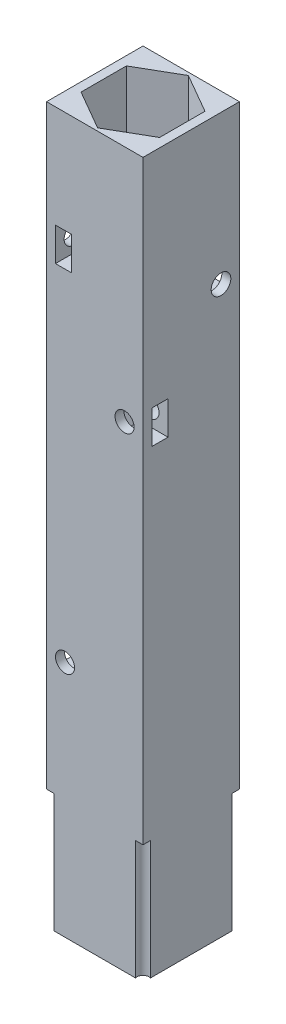
SolidWorks part; units mm, degrees
ref_plane "Спереди" through (0, 0, 0) normal (0, 0, 1) x (1, 0, 0)
ref_plane "Сверху" through (0, 0, 0) normal (0, 1, 0) x (1, 0, 0)
ref_plane "Справа" through (0, 0, 0) normal (1, 0, 0) x (0, 0, -1)
sketch "Эскиз1" plane through (0, 0, 0) normal (0, 1, 0) x (1, 0, 0)
  line L1 (-8.1, -8.1) -> (8.1, -8.1)
  line L2 (-8.1, -8.1) -> (-8.1, 8.1)
  line L3 (-8.1, 8.1) -> (8.1, 8.1)
  line L4 (8.1, -8.1) -> (8.1, 8.1)
  line L5 (-8.1, -8.1) -> (8.1, 8.1) construction
  line L6 (-8.1, 8.1) -> (8.1, -8.1) construction
  circle A0 centre (0, 0) radius 4
  point P0 (0, 0)
  dimension "D3" = 8
  dimension "D1" = 16.2
  dimension "D2" = 16.2
extrude "Бобышка-Вытянуть1" add sketch "Эскиз1" along normal blind 120
sketch "Эскиз2" plane through (0, 0, 0) normal (0, -1, 0) x (1, 0, 0)
  circle A0 centre (-7.8, -7.8) radius 1
  circle A1 centre (-7.8, 7.8) radius 1
  circle A2 centre (7.8, 7.8) radius 1
  circle A3 centre (7.8, -7.8) radius 1
  point P12 (0, 0)
  dimension "D1" = 2
  dimension "D2" = 7.8
  dimension "D3" = 7.8
  dimension "D4" = 4
extrude "Вырез-Вытянуть1" cut sketch "Эскиз2" against normal blind 20
sketch "Эскиз3" plane through (0, 120, 0) normal (0, 1, 0) x (1, 0, 0)
  line L1 (0, 7.621) -> (-6.6, 3.8105)
  line L2 (-6.6, 3.8105) -> (-6.6, -3.8105)
  line L3 (-6.6, -3.8105) -> (0, -7.621)
  line L4 (0, -7.621) -> (6.6, -3.8105)
  line L5 (6.6, -3.8105) -> (6.6, 3.8105)
  line L6 (6.6, 3.8105) -> (0, 7.621)
  circle A0 centre (0, 0) radius 6.6 construction
  dimension "D1" = 13.2
extrude "Вырез-Вытянуть2" cut sketch "Эскиз3" against normal blind 10
sketch "Эскиз4" plane through (0, 0, 8.1) normal (0, 0, 1) x (1, 0, 0)
  circle A0 centre (-5, 40) radius 1.6
  circle A1 centre (5, 80) radius 1.6
  dimension "D1" = 3.2
  dimension "D2" = 3.2
  dimension "D3" = 40
  dimension "D4" = 40
  dimension "D5" = 5
  dimension "D6" = 5
extrude "Вырез-Вытянуть3" cut sketch "Эскиз4" against normal blind 10
ref_plane "Плоскость1" through (0, 0, 6.6) normal (0, 0, 1) x (1, 0, 0)
sketch "Эскиз5" plane through (0, 0, 6.6) normal (0, 0, 1) x (1, 0, 0)
  line L0 (-6.6166, 42.8) -> (-8.1, 42.8)
  line L1 (-1.7668, 40) -> (-3.3834, 42.8)
  line L2 (-3.3834, 42.8) -> (-6.6166, 42.8)
  line L3 (8.1, 120) -> (8.1, 20) construction
  line L4 (-8.1, 120) -> (-8.1, 20) construction
  line L6 (-8.1, 42.8) -> (-8.1, 37.2)
  line L7 (6.6166, 82.8) -> (8.1, 82.8)
  line L8 (1.7668, 80) -> (3.3834, 77.2)
  line L9 (3.3834, 77.2) -> (6.6166, 77.2)
  line L10 (8.1, 82.8) -> (8.1, 77.2)
  line L11 (8.1, 77.2) -> (6.6166, 77.2)
  line L12 (6.6166, 82.8) -> (3.3834, 82.8)
  line L13 (-6.6166, 37.2) -> (-3.3834, 37.2)
  line L14 (-3.3834, 37.2) -> (-1.7668, 40)
  line L15 (-8.1, 37.2) -> (-6.6166, 37.2)
  line L16 (3.3834, 82.8) -> (1.7668, 80)
  line L17 (8.2332, 80) -> (6.6166, 82.8) [skipped]
  line L18 (6.6166, 77.2) -> (8.2332, 80) [skipped]
  line L24 (-6.6166, 42.8) -> (-8.2332, 40) [skipped]
  line L25 (-8.2332, 40) -> (-6.6166, 37.2) [skipped]
  circle A0 centre (-5, 40) radius 2.8 construction
  circle A1 centre (5, 80) radius 2.8 construction
extrude "Вырез-Вытянуть4" cut sketch "Эскиз5" against normal blind 2.7
sketch "Эскиз6" plane through (0, 0, -8.1) normal (0, 0, -1) x (-1, 0, 0)
  circle A0 centre (5, 105) radius 1.65
  dimension "D1" = 3.3
  dimension "D2" = 105
extrude "Вырез-Вытянуть5" cut sketch "Эскиз6" against normal blind 10
ref_plane "Плоскость2" through (0, 0, -6.6) normal (0, 0, -1) x (-1, 0, 0)
sketch "Эскиз7" plane through (0, 0, -6.6) normal (0, 0, -1) x (-1, 0, 0)
  line L0 (6.6166, 107.8) -> (8.1, 107.8)
  line L1 (1.7668, 105) -> (3.3834, 102.2)
  line L2 (3.3834, 102.2) -> (6.6166, 102.2)
  line L4 (8.1, 120) -> (8.1, 20) construction
  line L5 (8.1, 107.8) -> (8.1, 102.2)
  line L6 (6.6166, 107.8) -> (3.3834, 107.8)
  line L7 (3.3834, 107.8) -> (1.7668, 105)
  line L8 (8.1, 102.2) -> (6.6166, 102.2)
  line L12 (8.2332, 105) -> (6.6166, 107.8) [skipped]
  line L13 (6.6166, 102.2) -> (8.2332, 105) [skipped]
  circle A0 centre (5, 105) radius 2.8 construction
extrude "Вырез-Вытянуть6" cut sketch "Эскиз7" against normal blind 2.7
ref_plane "Плоскость3" through (-6.6, 0, 0) normal (-1, 0, 0) x (0, 0, 1)
ref_plane "Плоскость4" through (6.6, 0, 0) normal (1, 0, 0) x (0, 0, -1)
sketch "Эскиз9" plane through (-8.1, 0, 0) normal (-1, 0, 0) x (0, 0, 1)
  circle A0 centre (5, 100) radius 1.65
  dimension "D1" = 3.3
  dimension "D2" = 5
  dimension "D3" = 5
extrude "Вырез-Вытянуть7" cut sketch "Эскиз9" against normal blind 10
sketch "Эскиз10" plane through (-6.6, 0, 0) normal (-1, 0, 0) x (0, 0, 1)
  line L0 (6.6166, 102.8) -> (8.1, 102.8)
  line L1 (1.7668, 100) -> (3.3834, 97.2)
  line L2 (3.3834, 97.2) -> (6.6166, 97.2)
  line L3 (8.1, 120) -> (8.1, 20) construction
  line L4 (8.1, 102.8) -> (8.1, 97.2)
  line L5 (6.6166, 102.8) -> (3.3834, 102.8)
  line L6 (3.3834, 102.8) -> (1.7668, 100)
  line L7 (8.2332, 100) -> (6.6166, 102.8) [skipped]
  line L8 (6.6166, 97.2) -> (8.2332, 100) [skipped]
  line L9 (8.1, 97.2) -> (6.6166, 97.2)
  circle A0 centre (5, 100) radius 2.8 construction
extrude "Вырез-Вытянуть8" cut sketch "Эскиз10" against normal blind 2.7
sketch "Эскиз11" plane through (8.1, 0, 0) normal (1, 0, 0) x (0, 0, -1)
  line L0 (-8.1, 97.2) -> (-8.1, 102.8) construction
  circle A0 centre (5, 95) radius 1.65
  point P2 (-8.1, 100)
  dimension "D1" = 5
  dimension "D2" = 5
extrude "Вырез-Вытянуть9" cut sketch "Эскиз11" against normal blind 10
sketch "Эскиз12" plane through (6.6, 0, 0) normal (1, 0, 0) x (0, 0, -1)
  line L0 (6.6166, 97.8) -> (8.1, 97.8)
  line L1 (1.7668, 95) -> (3.3834, 92.2)
  line L2 (3.3834, 92.2) -> (6.6166, 92.2)
  line L3 (8.1, 120) -> (8.1, 20) construction
  line L4 (8.1, 97.8) -> (8.1, 92.2)
  line L5 (6.6166, 97.8) -> (3.3834, 97.8)
  line L6 (3.3834, 97.8) -> (1.7668, 95)
  line L7 (8.2332, 95) -> (6.6166, 97.8) [skipped]
  line L8 (6.6166, 92.2) -> (8.2332, 95) [skipped]
  line L9 (8.1, 92.2) -> (6.6166, 92.2)
  circle A0 centre (5, 95) radius 2.8 construction
extrude "Вырез-Вытянуть10" cut sketch "Эскиз12" against normal blind 2.7
